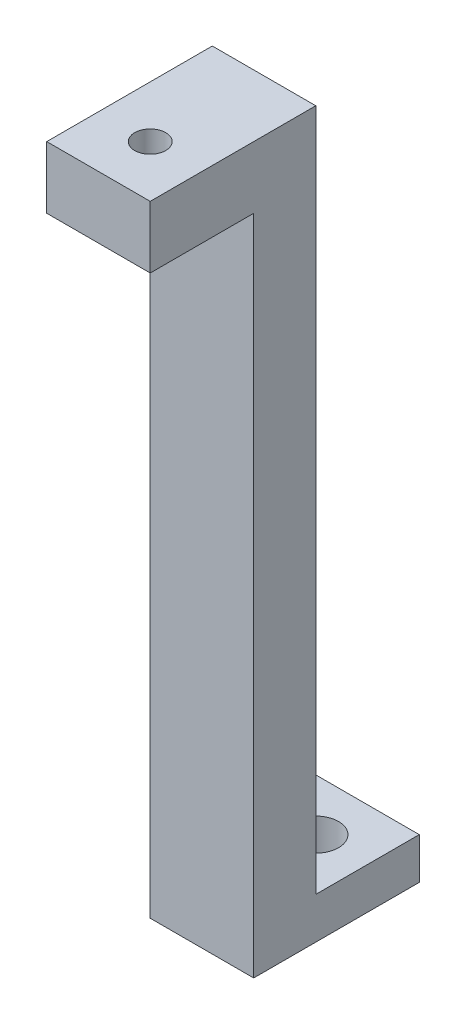
SolidWorks part; units mm, degrees
ref_plane "前视基准面" through (0, 0, 0) normal (0, 0, 1) x (1, 0, 0)
ref_plane "上视基准面" through (0, 0, 0) normal (0, 1, 0) x (1, 0, 0)
ref_plane "右视基准面" through (0, 0, 0) normal (1, 0, 0) x (0, 0, -1)
other "Configuration Table"
sketch "草图1" plane through (0, 0, 0) normal (0, 1, 0) x (1, 0, 0)
  line L22 (-2.5, -2.5) -> (2.5, -2.5)
  line L23 (-2.5, -2.5) -> (-2.5, 2.5)
  line L28 (-2.5, 2.5) -> (2.5, 2.5)
  line L29 (2.5, -2.5) -> (2.5, 2.5)
  line L37 (-2.5, -2.5) -> (2.5, 2.5) construction
  line L38 (-2.5, 2.5) -> (2.5, -2.5) construction
  circle A7 centre (0, 0) radius 1.1
  point P0 (0, 0)
  dimension "D4" = 2.2
  dimension "D2" = 5
extrude "凸台-拉伸1" add sketch "草图1" along normal blind 2
sketch "草图2" plane through (0, 0, 0) normal (0, -1, 0) x (1, 0, 0)
  line L1 (-2.5, 2.5) -> (2.5, 2.5)
  line L2 (-2.5, 2.5) -> (-2.5, 5.5)
  line L3 (-2.5, 5.5) -> (2.5, 5.5)
  line L4 (2.5, 2.5) -> (2.5, 5.5)
  line L5 (2.5, 2.5) -> (2.5, -2.5) construction
  point P4 (0, 0)
  point P5 (2.5, 2.5)
  point P7 (-2.5, 2.5)
  dimension "D1" = 3
extrude "凸台-拉伸2" add sketch "草图2" against normal blind 35
sketch "草图3" plane through (0, 35, 0) normal (0, 1, 0) x (1, 0, 0)
  line L1 (-2.5, -5.5) -> (2.5, -5.5)
  line L2 (-2.5, -5.5) -> (-2.5, -10.5)
  line L3 (-2.5, -10.5) -> (2.5, -10.5)
  line L4 (2.5, -5.5) -> (2.5, -10.5)
  circle A0 centre (0, -8) radius 0.75
  point P5 (-2.5, -8)
  point P9 (0, -10.5)
  dimension "D1" = 1.5
extrude "凸台-拉伸3" add sketch "草图3" against normal blind 3
